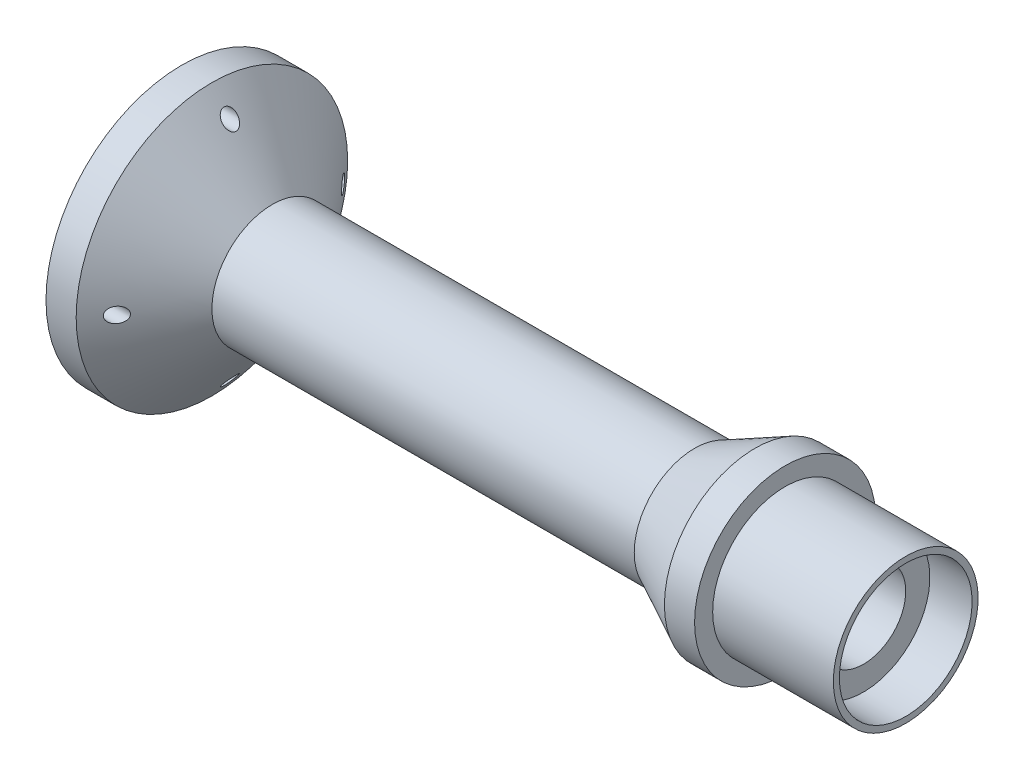
SolidWorks part; units mm, degrees
ref_plane "Ön Düzlem" through (0, 0, 0) normal (0, 0, 1) x (1, 0, 0)
ref_plane "Üst Düzlem" through (0, 0, 0) normal (0, 1, 0) x (1, 0, 0)
ref_plane "Sağ Düzlem" through (0, 0, 0) normal (1, 0, 0) x (0, 0, -1)
sketch "Çizim2" plane through (0, 0, 0) normal (0, 0, 1) x (1, 0, 0)
  line L0 (0, 0) -> (92.4214, 0) construction
  line L1 (-14.2227, 7) -> (98.7773, 7)
  line L2 (-14.2227, 7) -> (-14.2227, 22.5)
  line L3 (-14.2227, 22.5) -> (-9.2227, 22.5)
  line L4 (-9.2227, 22.5) -> (0.7773, 10)
  line L5 (0.7773, 10) -> (70.7773, 10)
  line L6 (70.7773, 10) -> (80.7773, 15)
  line L7 (80.7773, 15) -> (85.7773, 15)
  line L8 (85.7773, 15) -> (85.7773, 12)
  line L9 (85.7773, 12) -> (105.7773, 12)
  line L10 (105.7773, 12) -> (105.7773, 11)
  line L11 (98.7773, 7) -> (98.7773, 11)
  line L12 (98.7773, 11) -> (105.7773, 11)
  dimension "D2" = 5
  dimension "D3" = 10
  dimension "D4" = 20
  dimension "D5" = 25
  dimension "D6" = 10
  dimension "D7" = 3
  dimension "D8" = 5
  dimension "D9" = 15
  dimension "D10" = 22.5
  dimension "D11" = 7
  dimension "D12" = 11
  dimension "D13" = 3
revolve "Döndür1" add sketch "Çizim2" angle 360 about L0
sketch "Çizim3" plane through (-14.2227, 0, 0) normal (-1, 0, 0) x (0, 0, 1)
  circle A0 centre (0, 18.75) radius 1.25
  dimension "D1" = 2.5
  dimension "D2" = 18.75
extrude "Kes-Ekstrüzyon1" cut sketch "Çizim3" against normal blind 10
pattern_circular "Dairesel Kaplama2" count 4 over 360 about axis through (0, 0, 0) along (1, 0, 0) of "Kes-Ekstrüzyon1"
